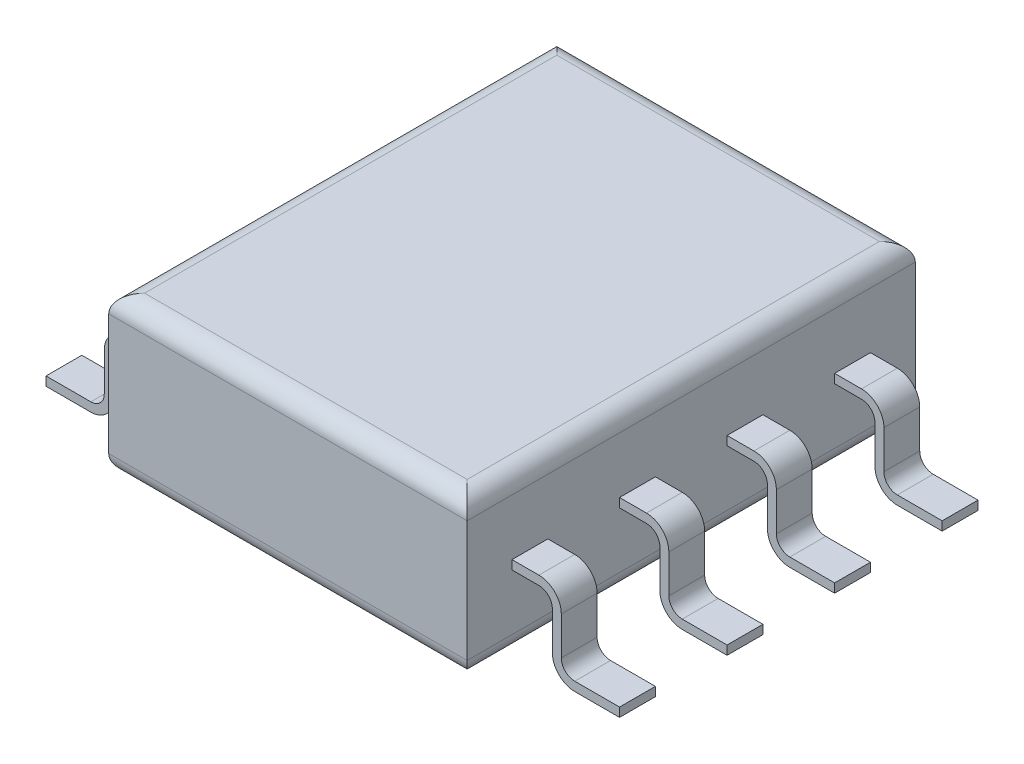
SolidWorks part; units mm, degrees
ref_plane "Front" through (0, 0, 0) normal (0, 0, 1) x (1, 0, 0)
ref_plane "Top" through (0, 0, 0) normal (0, 1, 0) x (1, 0, 0)
ref_plane "Right" through (0, 0, 0) normal (1, 0, 0) x (0, 0, -1)
sketch "Sketch1" plane through (0, 0, 0) normal (0, 1, 0) x (1, 0, 0)
  line L1 (-2, -2.5) -> (2, -2.5)
  line L2 (-2, -2.5) -> (-2, 2.5)
  line L3 (-2, 2.5) -> (2, 2.5)
  line L4 (2, -2.5) -> (2, 2.5)
  line L5 (-2, -2.5) -> (2, 2.5) construction
  line L6 (-2, 2.5) -> (2, -2.5) construction
  point P0 (0, 0)
  dimension "D1" = 4
  dimension "D2" = 5
extrude "Boss-Extrude1" add sketch "Sketch1" along normal blind 1.75
fillet "Fillet1" radius 0.2 8 edges at (0, 0, -2.5) (-2, 0, 0) (0, 0, 2.5) (2, 0, 0) (0, 1.75, -2.5) (2, 1.75, 0) (0, 1.75, 2.5) (-2, 1.75, 0)
ref_plane "Plane1" through (0, 0, -1.8) normal (0, 0, -1) x (-1, 0, 0)
sketch "Sketch2" plane through (0, 0, -1.8) normal (0, 0, -1) x (-1, 0, 0)
  line L0 (2, 0.875) -> (2.3, 0.875)
  line L1 (2.5, 0.675) -> (2.5, 0.25)
  line L2 (2.7, 0.05) -> (3.2, 0.05)
  line L3 (-1.8, 0) -> (1.8, 0) construction
  line L4 (2, 1.55) -> (2, 0.2) construction
  arc A0 (2.5, 0.25) -> (2.7, 0.05) centre (2.7, 0.25) ccw
  arc A1 (2.3, 0.875) -> (2.5, 0.675) centre (2.3, 0.675) cw
  point P10 (2.5, 0.05)
  point P13 (2.5, 0.875)
  dimension "D4" = 0.2
  dimension "D1" = 0.5
  dimension "D2" = 0.05
  dimension "D3" = 0.7
sketch "Sketch3" plane through (-2, 0, 0) normal (-1, 0, 0) x (0, 0, 1)
  line L1 (-2, 0.825) -> (-1.6, 0.825)
  line L2 (-2, 0.825) -> (-2, 0.925)
  line L3 (-2, 0.925) -> (-1.6, 0.925)
  line L4 (-1.6, 0.825) -> (-1.6, 0.925)
  line L5 (-2, 0.825) -> (-1.6, 0.925) construction
  line L6 (-2, 0.925) -> (-1.6, 0.825) construction
  point P0 (-1.8, 0.875)
  dimension "D1" = 0.1
  dimension "D2" = 0.4
sweep "Sweep1" add profiles "Sketch3" path "Sketch2"
pattern_linear "LPattern1" count 4 spacing 1.2 along (0, 0, 1) of "Sweep1"
mirror "Mirror1" about plane through (0, 0, 0) normal (1, 0, 0) of "LPattern1", "Sweep1"
